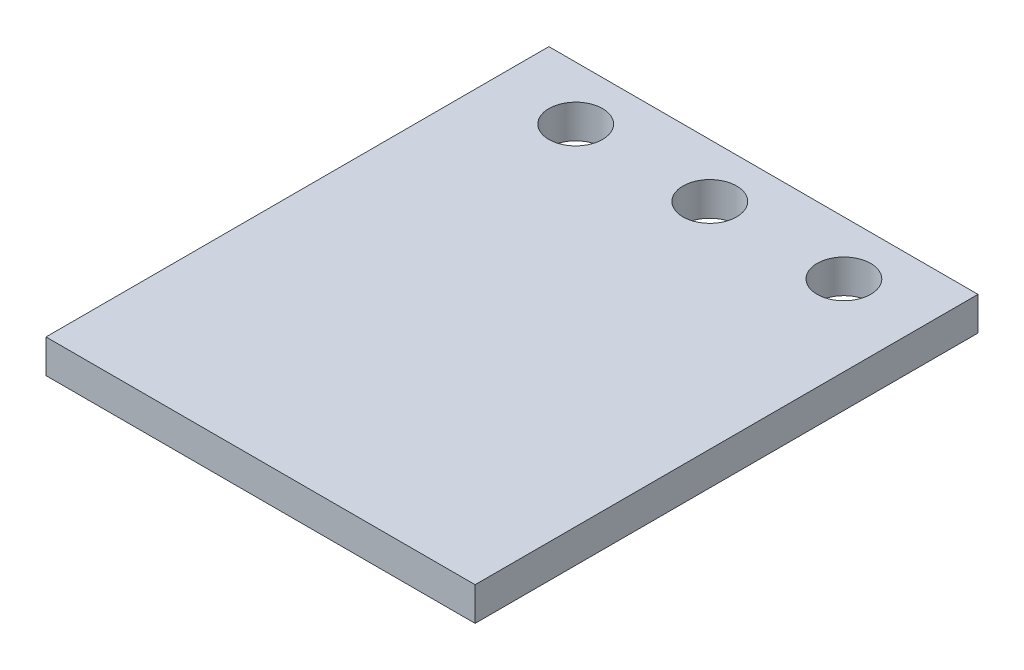
SolidWorks part; units mm, degrees
ref_plane "Alzado" through (0, 0, 0) normal (0, 0, 1) x (1, 0, 0)
ref_plane "Planta" through (0, 0, 0) normal (0, 1, 0) x (1, 0, 0)
ref_plane "Vista lateral" through (0, 0, 0) normal (1, 0, 0) x (0, 0, -1)
ref_plane "Plano1" through (0, 0, 360) normal (0, 0, -1) x (-1, 0, 0)
sketch "Croquis2" plane through (0, 0, 360) normal (0, 0, -1) x (-1, 0, 0)
  line L0 (7.7541, 182.0598) -> (7.7541, 202.8344) construction
  line L1 (192.7541, 202.8344) -> (-177.2459, 202.8344) construction
  line L2 (7.7541, 202.8344) -> (7.7541, 222.538) construction
  line L3 (-152.2459, 202.8344) -> (167.7541, 202.8344)
  line L4 (-152.2459, 202.8344) -> (-152.2459, 177.8344)
  line L5 (-152.2459, 177.8344) -> (167.7541, 177.8344)
  line L6 (167.7541, 202.8344) -> (167.7541, 177.8344)
  point P4 (7.7541, 182.0598)
  dimension "D1" = 320
  dimension "D2" = 25
extrude "Saliente-Extruir1" add sketch "Croquis2" along normal blind 375
sketch "Croquis3" plane through (0, 202.8344, 0) normal (0, 1, 0) x (1, 0, 0)
  line L0 (-7.7541, 15) -> (-7.7541, -25) construction
  line L1 (-167.7541, 15) -> (152.2459, 15) construction
  circle A0 centre (-107.7541, -25) radius 20
  circle A1 centre (-7.7541, -25) radius 20
  circle A2 centre (92.2459, -25) radius 20
  point P7 (-7.7541, -5)
  dimension "D3" = 40
  dimension "D1" = 20
  dimension "D4" = 100
  dimension "D2" = 3
extrude "Cortar-Extruir1" cut sketch "Croquis3" against normal up to next
